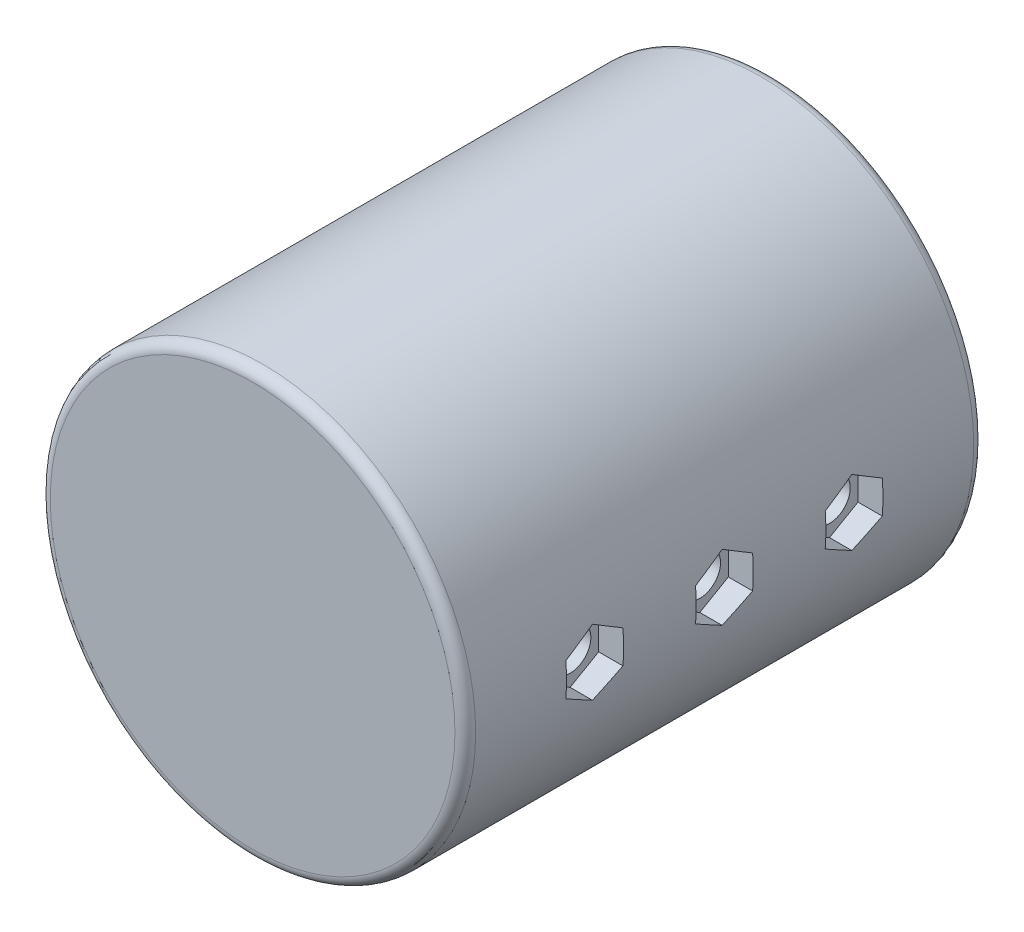
SolidWorks part; units mm, degrees
material "ABS"
ref_plane "Спереди" through (0, 0, 0) normal (0, 0, 1) x (1, 0, 0)
ref_plane "Сверху" through (0, 0, 0) normal (0, 1, 0) x (1, 0, 0)
ref_plane "Справа" through (0, 0, 0) normal (1, 0, 0) x (0, 0, -1)
other "Configuration Table"
sketch "Эскиз1" plane through (0, 0, 0) normal (0, 0, 1) x (1, 0, 0)
  circle A0 centre (0, 0) radius 20.5
  dimension "D1" = 41
extrude "Бобышка-Вытянуть1" add sketch "Эскиз1" along normal blind 50
fillet "Скругление1" radius 1 1 edges at (20.5, 0, 50)
fillet "Скругление2" radius 1 1 edges at (20.5, 0, 0)
ref_plane "Плоскость1" through (20.5, 0, 0) normal (1, 0, 0) x (0, 0, -1)
sketch "Эскиз2" plane through (20.5, 0, 0) normal (1, 0, 0) x (0, 0, -1)
  line L0 (-50, 19.5) -> (-50, -19.5) construction
  line L1 (-49, -20.5) -> (-1, -20.5) construction
  circle A0 centre (-37.5, 0) radius 2
  circle A1 centre (-25, 0) radius 2
  circle A2 centre (-12.5, 0) radius 2
  point P8 (-30.9457, 6.3924)
  point P9 (-17.1855, 6.9631)
  point P10 (-14.9661, 6.3924)
  point P11 (-26.1899, 6.3924)
  point P12 (-26.7606, 0)
  point P13 (-7.3568, 0)
  point P14 (-24.8583, 0)
  point P15 (0, 0)
  point P17 (-20.6731, 4.9974)
  dimension "D1" = 4
  dimension "D2" = 4
  dimension "D3" = 4
  dimension "D4" = 12.5
  dimension "D5" = 12.5
  dimension "D6" = 12.5
  dimension "D7" = 20.5
  dimension "D8" = 20.5
  dimension "D9" = 20.5
extrude "Вырез-Вытянуть1" cut sketch "Эскиз2" against normal through all
sketch "Эскиз3" plane through (20.5, 0, 0) normal (1, 0, 0) x (0, 0, -1)
  line L0 (-50, 19.5) -> (-50, -19.5) construction
  line L8 (-25, 3.1754) -> (-27.75, 1.5877)
  line L9 (-37.5, 3.1754) -> (-40.25, 1.5877)
  line L10 (-40.25, 1.5877) -> (-40.25, -1.5877)
  line L11 (-40.25, -1.5877) -> (-37.5, -3.1754)
  line L12 (-37.5, -3.1754) -> (-34.75, -1.5877)
  line L13 (-34.75, -1.5877) -> (-34.75, 1.5877)
  line L14 (-34.75, 1.5877) -> (-37.5, 3.1754)
  line L15 (-27.75, 1.5877) -> (-27.75, -1.5877)
  line L16 (-27.75, -1.5877) -> (-25, -3.1754)
  line L17 (-25, -3.1754) -> (-22.25, -1.5877)
  line L18 (-22.25, -1.5877) -> (-22.25, 1.5877)
  line L19 (-22.25, 1.5877) -> (-25, 3.1754)
  line L20 (-12.5, 3.1754) -> (-15.25, 1.5877)
  line L21 (-15.25, 1.5877) -> (-15.25, -1.5877)
  line L22 (-15.25, -1.5877) -> (-12.5, -3.1754)
  line L23 (-12.5, -3.1754) -> (-9.75, -1.5877)
  line L24 (-9.75, -1.5877) -> (-9.75, 1.5877)
  line L25 (-9.75, 1.5877) -> (-12.5, 3.1754)
  circle A0 centre (-37.5, 0) radius 2.75 construction
  circle A1 centre (-25, 0) radius 2.75 construction
  circle A2 centre (-12.5, 0) radius 2.75 construction
  point P19 (-37.0909, 3.1754)
  point P30 (-37.5, 3.1754)
  dimension "D4" = 5.5
  dimension "D5" = 5.5
  dimension "D6" = 5.5
  dimension "D7" = 12.5
  dimension "D8" = 12.5
  dimension "D9" = 12.5
extrude "Вырез-Вытянуть2" cut sketch "Эскиз3" against normal blind 2.4
mirror "Зеркальное отражение1" about plane through (0, 0, 0) normal (1, 0, 0) of "Вырез-Вытянуть2"
